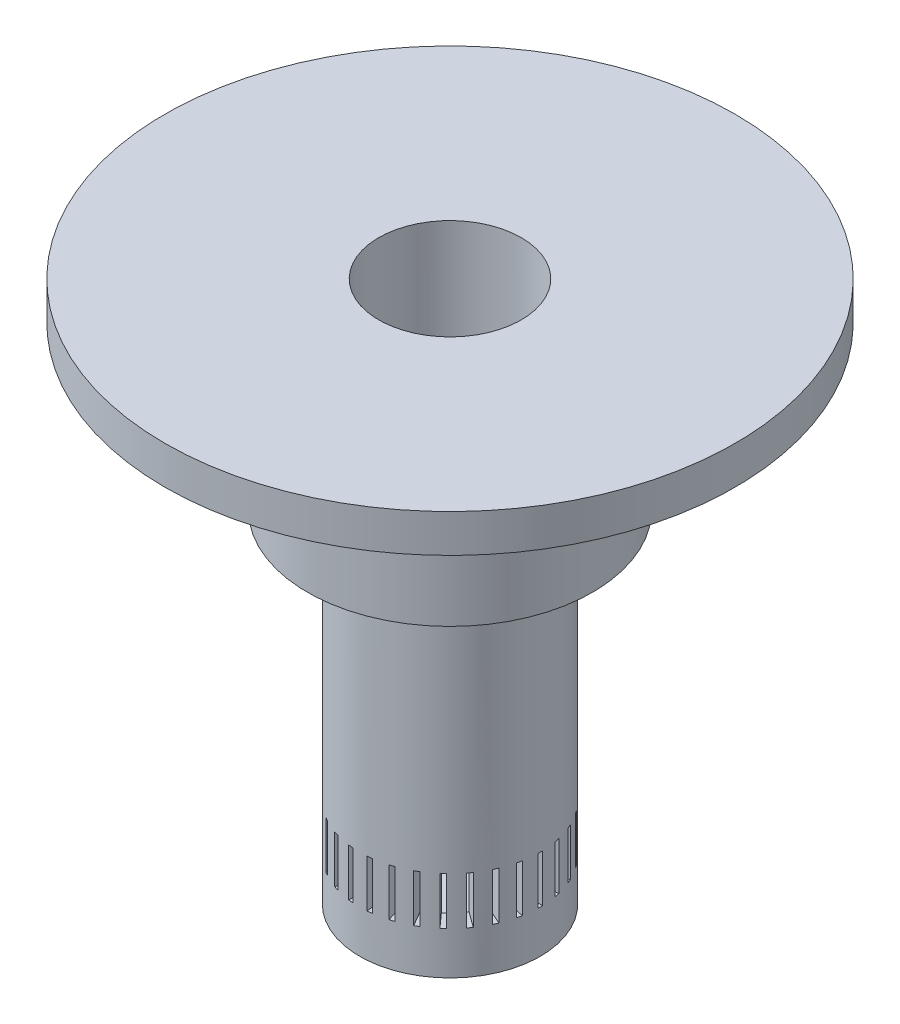
SolidWorks part; units mm, degrees
ref_plane "Front Plane" through (0, 0, 0) normal (0, 0, 1) x (1, 0, 0)
ref_plane "Top Plane" through (0, 0, 0) normal (0, 1, 0) x (1, 0, 0)
ref_plane "Right Plane" through (0, 0, 0) normal (1, 0, 0) x (0, 0, -1)
sketch "Sketch3" plane through (0, 0, 0) normal (0, 0, 1) x (1, 0, 0)
  line L0 (0, 0) -> (0, 92.2215) construction
  line L1 (-38.1, 16.3004) -> (-38.1, 11.2204)
  line L2 (-38.1, 11.2204) -> (-19.05, 11.2204)
  line L3 (-19.05, 11.2204) -> (-19.05, 1.6954)
  line L4 (-19.05, 1.6954) -> (-15.24, 1.6954)
  line L5 (-15.24, 1.6954) -> (-15.24, -1.4796)
  line L6 (-15.24, -1.4796) -> (-19.05, -1.4796)
  line L7 (-19.05, -1.4796) -> (-19.05, -10.4657)
  line L8 (-19.05, -10.4657) -> (-12.065, -14.1796)
  line L9 (-12.065, -14.1796) -> (-12.065, -56.0896)
  line L10 (-12.065, -56.0896) -> (0, -56.0896)
  line L11 (0, -56.0896) -> (0, -52.2796)
  line L12 (0, -52.2796) -> (-9.525, -52.2796)
  line L13 (-9.525, -52.2796) -> (-9.525, 16.3004)
  line L14 (-9.525, 16.3004) -> (-38.1, 16.3004)
  dimension "D1" = 19.05
  dimension "D2" = 24.13
  dimension "D3" = 3.175
  dimension "D4" = 3.81
  dimension "D5" = 19.05
  dimension "D6" = 41.91
  dimension "D7" = 38.1
  dimension "D8" = 38.1
  dimension "D9" = 5.08
  dimension "D10" = 19.05
  dimension "D11" = 25.4
  dimension "D12" = 12.7
  dimension "D13" = 118
revolve "Revolve1" add sketch "Sketch3" angle 360 about L0
ref_plane "Plane1" through (12.065, 0, 0) normal (1, 0, 0) x (0, 0, -1)
sketch "Sketch4" plane through (12.065, 0, 0) normal (1, 0, 0) x (0, 0, -1)
  line L0 (0, -56.0896) -> (0, -26.7795) construction
  line L1 (-12.065, -56.0896) -> (12.065, -56.0896) construction
  line L3 (-0.3175, -50.3746) -> (0.3175, -50.3746)
  line L4 (-0.3175, -50.3746) -> (-0.3175, -44.0246)
  line L5 (-0.3175, -44.0246) -> (0.3175, -44.0246)
  line L6 (0.3175, -50.3746) -> (0.3175, -44.0246)
  line L7 (-0.3175, -50.3746) -> (0.3175, -44.0246) construction
  line L8 (-0.3175, -44.0246) -> (0.3175, -50.3746) construction
  circle A0 centre (0, -47.1996) radius 0.762 construction
  dimension "D1" = 1.524
  dimension "D2" = 8.89
  dimension "D3" = 0.635
  dimension "D4" = 6.35
extrude "Cut-Extrude2" cut sketch "Sketch4" against normal blind 6.35
pattern_circular "CirPattern1" count 30 every 12 about axis through (0, 0, 0) along (0, 1, 0) of "Cut-Extrude2"
